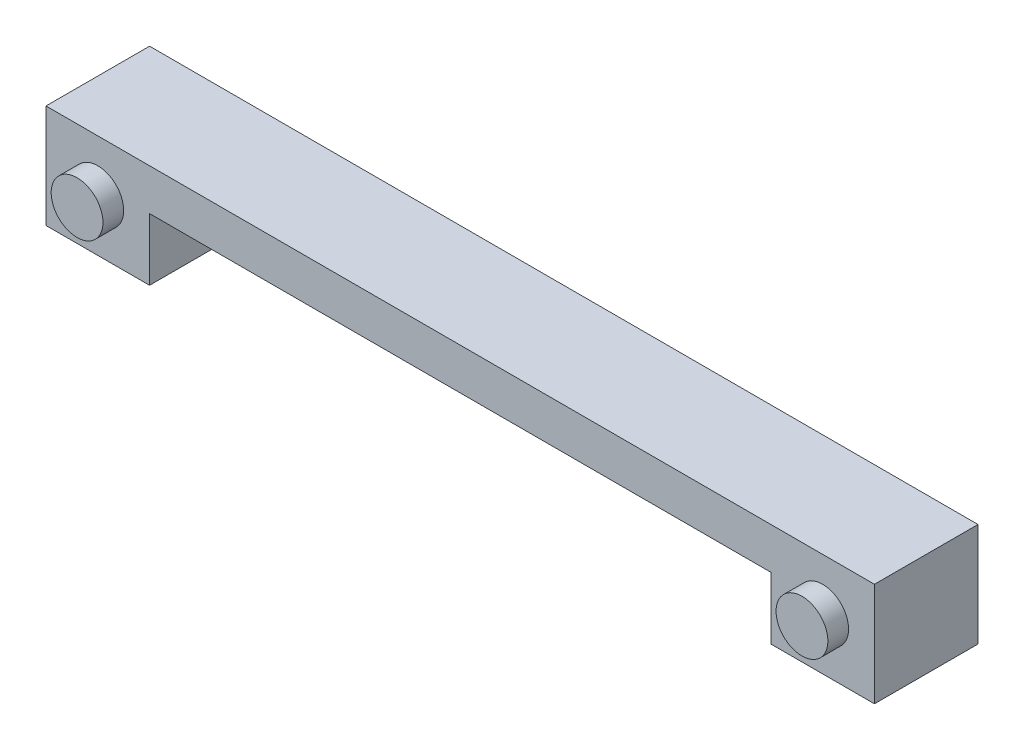
SolidWorks part; units mm, degrees
ref_plane "Front Plane" through (0, 0, 0) normal (0, 0, 1) x (1, 0, 0)
ref_plane "Top Plane" through (0, 0, 0) normal (0, 1, 0) x (1, 0, 0)
ref_plane "Right Plane" through (0, 0, 0) normal (1, 0, 0) x (0, 0, -1)
sketch "Sketch1" plane through (0, 0, 0) normal (0, 0, 1) x (1, 0, 0)
  line L1 (0, 0) -> (6.35, 0)
  line L2 (0, 0) -> (0, 6.35)
  line L3 (0, 6.35) -> (6.35, 6.35)
  line L4 (6.35, 0) -> (6.35, 6.35)
  line L5 (6.35, 6.35) -> (25.4, 6.35)
  line L6 (6.35, 6.35) -> (6.35, 3.81)
  line L7 (6.35, 3.81) -> (25.4, 3.81)
  line L8 (25.4, 6.35) -> (25.4, 3.81)
  dimension "D1" = 25.4
  dimension "D2" = 6.35
  dimension "D3" = 6.35
  dimension "D4" = 2.54
extrude "Boss-Extrude1" add sketch "Sketch1" along normal blind 6.35 contours L1 L4 L3 L2 | L8 L5 L4 L7
sketch "Sketch2" plane through (0, 0, 6.35) normal (0, 0, 1) x (1, 0, 0)
  line L0 (0, 0) -> (6.35, 0) construction
  line L1 (0, 0) -> (0, 6.35) construction
  circle A0 centre (3.175, 3.175) radius 1.5875
  point P2 (0, 0)
  point P5 (3.175, 0)
  point P6 (0, 0)
  point P9 (0, 3.175)
  dimension "D1" = 3.175
extrude "Boss-Extrude2" add sketch "Sketch2" along normal blind 1.27 contours A0
mirror "Mirror1" about plane through (25.4, 0, 6.35) normal (1, 0, 0) of "Boss-Extrude2", "Boss-Extrude1"
